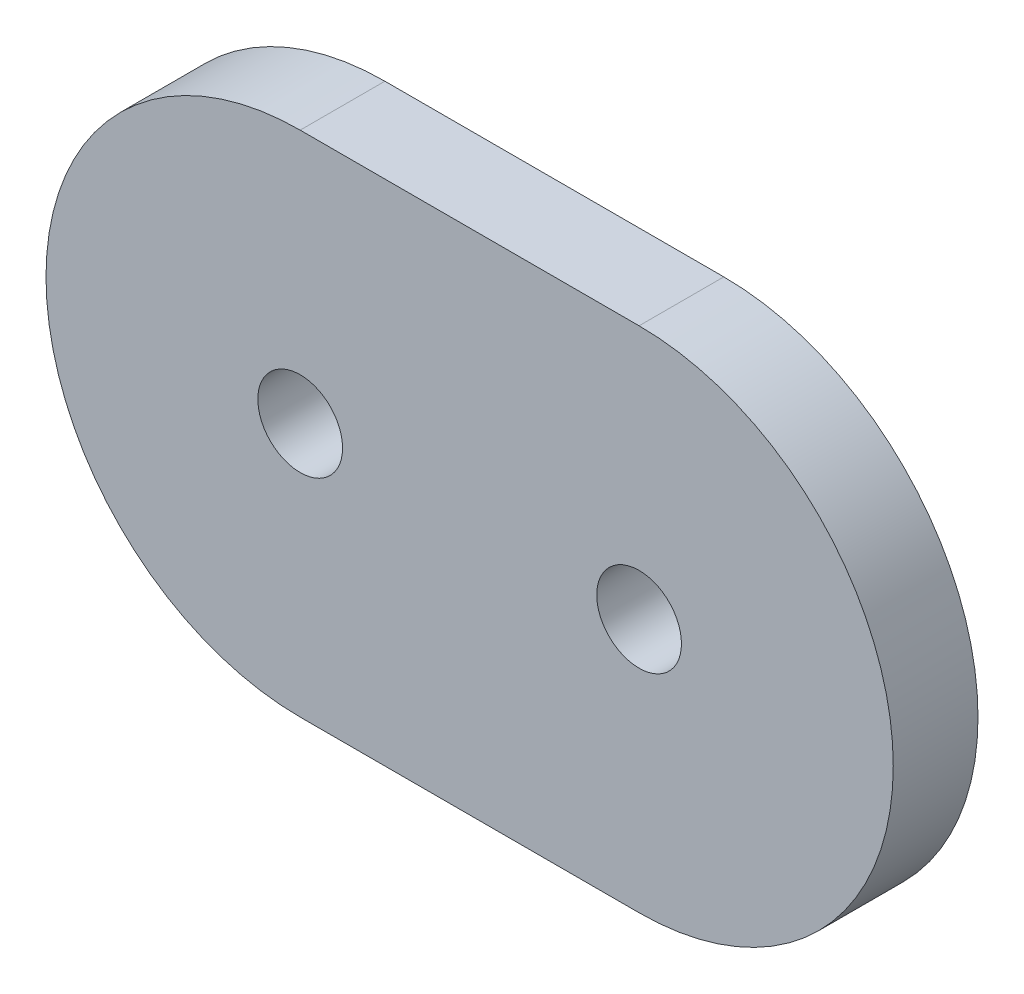
SolidWorks part; units mm, degrees
ref_plane "Спереди" through (0, 0, 0) normal (0, 0, 1) x (1, 0, 0)
ref_plane "Сверху" through (0, 0, 0) normal (0, 1, 0) x (1, 0, 0)
ref_plane "Справа" through (0, 0, 0) normal (1, 0, 0) x (0, 0, -1)
sketch "Sketch1" plane through (0, 0, 0) normal (0, 0, 1) x (1, 0, 0)
  line L0 (0, 0) -> (-4.3548, 0) construction
  line L1 (-4.3548, 0) -> (4.5161, 0) construction
  line L2 (-4.3548, 1.5) -> (-2.3548, 1.5)
  line L3 (-4.3548, -1.5) -> (-2.3548, -1.5)
  arc A0 (-4.3548, 1.5) -> (-4.3548, -1.5) centre (-4.3548, 0) ccw
  arc A1 (-2.3548, 1.5) -> (-2.3548, -1.5) centre (-2.3548, 0) cw
  circle A2 centre (-4.3548, 0) radius 0.25
  circle A3 centre (-2.3548, 0) radius 0.25
  dimension "D3" = 0.5
  dimension "D4" = 0.5
  dimension "D1" = 1.5
  dimension "D2" = 2
extrude "Boss-Extrude1" add sketch "Sketch1" along normal blind 0.5
